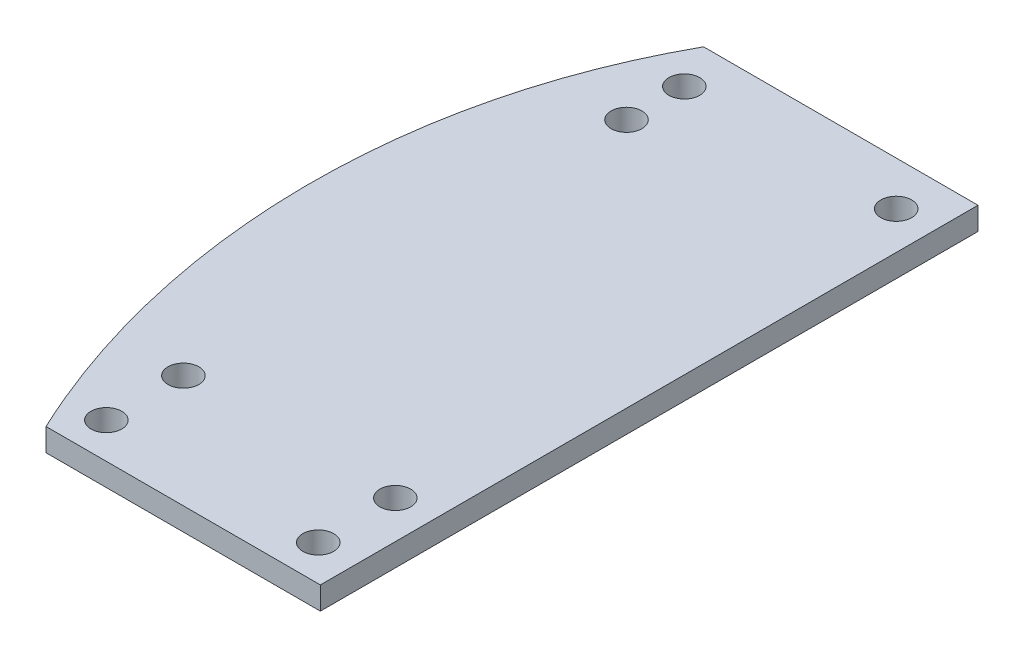
SolidWorks part; units mm, degrees
ref_plane "Front" through (0, 0, 0) normal (0, 0, 1) x (1, 0, 0)
ref_plane "Top" through (0, 0, 0) normal (0, 1, 0) x (1, 0, 0)
ref_plane "Right" through (0, 0, 0) normal (1, 0, 0) x (0, 0, -1)
sketch "Sketch1" plane through (0, 0, 0) normal (0, 1, 0) x (1, 0, 0)
  line L0 (-8.088, -17.8579) -> (20.3966, -17.8579)
  line L1 (20.3966, -86.1274) -> (20.3966, -17.8579)
  line L2 (20.3966, -86.1274) -> (-8.088, -86.1274)
  spline S1 degree 3 poles (-8.088, -17.8579) (-19.8235, -38.981) (-18.0628, -64.9857) (-8.088, -86.1274) knots 0 0 0 0 1 1 1 1
  point P18 (0, 0)
extrude "Boss-Extrude1" add sketch "Sketch1" along normal blind 1 and the other way blind 1.3622
sketch "Sketch15" plane through (0, 1, 0) normal (0, 1, 0) x (1, 0, 0)
  line L0 (-5.5276, -22.4235) -> (-5.5276, -82.4235) construction
  line L1 (-5.5276, -82.4235) -> (16.4724, -82.4235) construction
  line L2 (16.4724, -82.4235) -> (16.4724, -22.4235) construction
  line L3 (16.4724, -22.4235) -> (-5.5276, -22.4235) construction
  line L4 (-5.5276, -74.4235) -> (16.4724, -74.4235) construction
  line L5 (1.0842, -22.4235) -> (1.0842, -28.4235) construction
  line L6 (1.0842, -28.4235) -> (-5.5276, -28.4235) construction
  circle A0 centre (-5.5276, -22.4235) radius 1.6
  circle A1 centre (16.4724, -22.4235) radius 1.6
  circle A2 centre (-5.5276, -82.4235) radius 1.6
  circle A3 centre (16.4724, -82.4235) radius 1.6
  circle A4 centre (-5.5276, -74.4235) radius 1.6
  circle A5 centre (16.4724, -74.4235) radius 1.6
  circle A6 centre (-5.5276, -28.4235) radius 1.6
  dimension "D3" = 52
  dimension "D1" = 60
  dimension "D2" = 22
extrude "Cut-Extrude1" cut sketch "Sketch15" against normal blind 10
sketch "Sketch16" plane through (0, 1, 0) normal (0, 1, 0) x (1, 0, 0)
